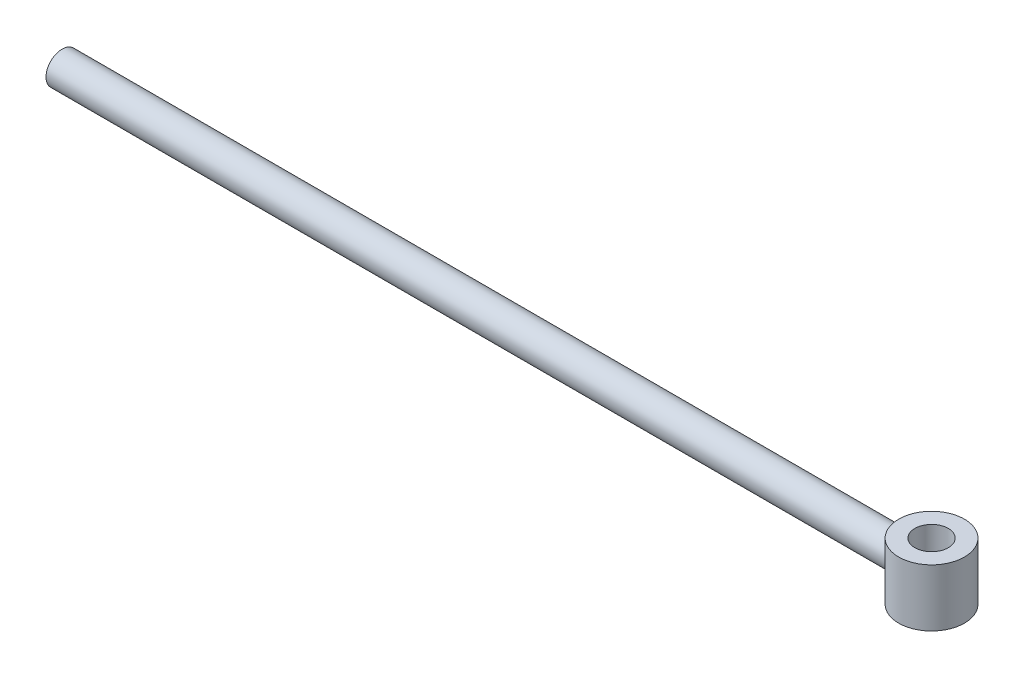
SolidWorks part; units mm, degrees
ref_plane "Front Plane" through (0, 0, 0) normal (0, 0, 1) x (1, 0, 0)
ref_plane "Top Plane" through (0, 0, 0) normal (0, 1, 0) x (1, 0, 0)
ref_plane "Right Plane" through (0, 0, 0) normal (1, 0, 0) x (0, 0, -1)
ref_plane "Plane1" through (0, 63.5, 0) normal (0, 1, 0) x (1, 0, 0)
ref_axis "Axis1" through (38.1, 50.8, -139.7) along (0, -1, 0)
ref_plane "Plane2" through (38.1, 0, 0) normal (-1, 0, 0) x (0, -1, 0)
sketch "Sketch2" plane through (38.1, 0, 0) normal (-1, 0, 0) x (0, -1, 0)
  line L0 (-38.1, -133.35) -> (-63.5, -133.35) construction
  line L1 (-60.96, -126.746) -> (-38.354, -126.746)
  line L2 (-60.96, -126.746) -> (-60.96, -133.096)
  line L3 (-60.96, -133.096) -> (-38.354, -133.096)
  line L4 (-38.354, -126.746) -> (-38.354, -133.096)
  line L5 (-63.5, -133.35) -> (-63.5, -146.05) construction
  line L6 (-38.1, -127) -> (-38.1, -152.4) construction
  dimension "D1" = 0.254
  dimension "D2" = 2.54
  dimension "D3" = 0.254
  dimension "D4" = 6.35
revolve "Revolve1" add sketch "Sketch2" angle 360 about axis through (38.1, 50.8, -139.7) along (0, -1, 0)
sketch "Sketch3" plane through (0, 0, 0) normal (-1, 0, 0) x (0, 0, 1)
  line L0 (-139.7, 50.8) -> (-139.7, 25.4) construction
  line L1 (-126.746, 60.96) -> (-152.654, 60.96) construction
  circle A0 centre (-139.7, 50.165) radius 6.35
  dimension "D1" = 12.7
  dimension "D2" = 10.795
extrude "Boss-Extrude1" add sketch "Sketch3" along normal blind 304.8 and the other way up to surface
